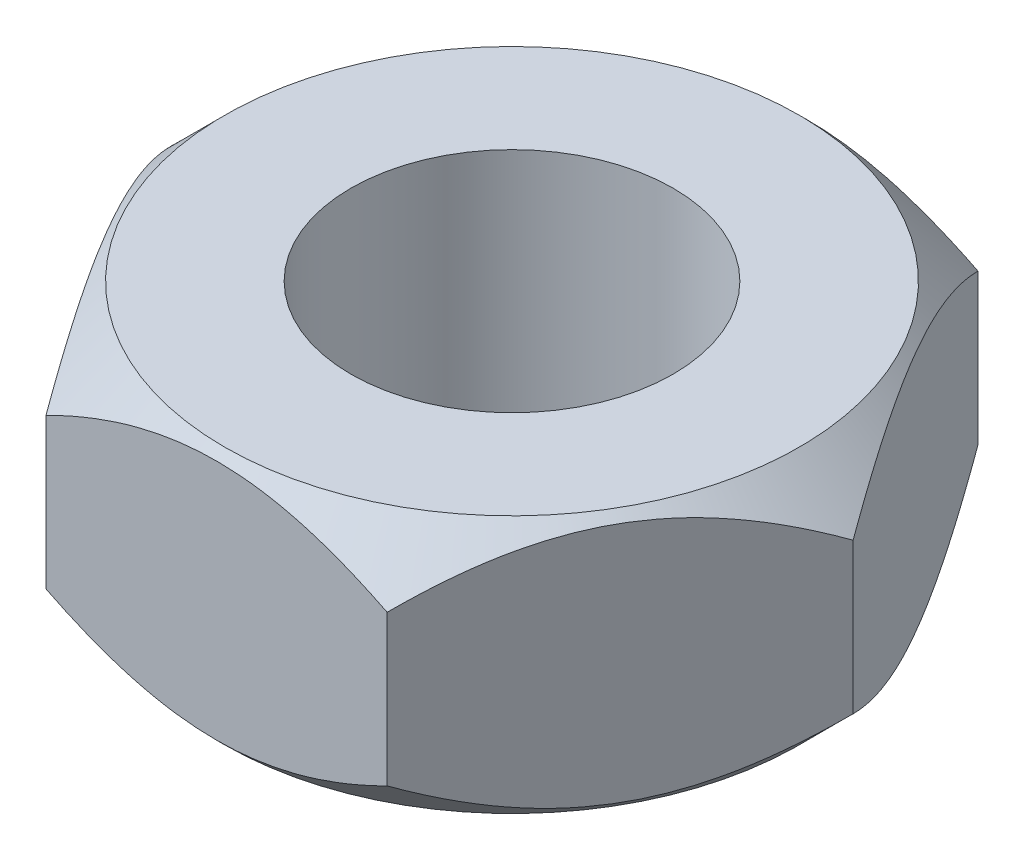
SolidWorks part; units mm, degrees
material "AISI 304"
ref_plane "Front Plane" through (0, 0, 0) normal (0, 0, 1) x (1, 0, 0)
ref_plane "Top Plane" through (0, 0, 0) normal (0, 1, 0) x (1, 0, 0)
ref_plane "Right Plane" through (0, 0, 0) normal (1, 0, 0) x (0, 0, -1)
sketch "Sketch1" plane through (0, 0, 0) normal (0, 1, 0) x (1, 0, 0)
  line L1 (1.5877, 2.75) -> (-1.5877, 2.75)
  line L2 (-1.5877, 2.75) -> (-3.1754, 0)
  line L3 (-3.1754, 0) -> (-1.5877, -2.75)
  line L4 (-1.5877, -2.75) -> (1.5877, -2.75)
  line L5 (1.5877, -2.75) -> (3.1754, 0)
  line L6 (3.1754, 0) -> (1.5877, 2.75)
  circle A0 centre (0, 0) radius 2.75 construction
  circle A1 centre (0, 0) radius 1.5
  dimension "D2" = 3
  dimension "D1" = 5.5
extrude "Boss-Extrude1" add sketch "Sketch1" along normal blind 2.4
sketch "Sketch2" plane through (0, 0, 0) normal (0, 0, 1) x (1, 0, 0)
  line L0 (3.1754, 0) -> (3.1754, 0.5)
  line L1 (3.1754, 2.4) -> (3.1754, 0) construction
  line L2 (3.1754, 0.5) -> (2.6754, 0)
  line L3 (2.6754, 0) -> (3.1754, 0)
  line L4 (1.5877, 1.2) -> (50001.5877, 1.2) construction
  line L5 (1.5877, 2.4) -> (1.5877, 0) construction
  line L6 (2.6754, 2.4) -> (3.1754, 2.4)
  line L7 (3.1754, 1.9) -> (2.6754, 2.4)
  line L8 (3.1754, 2.4) -> (3.1754, 1.9)
  point P10 (1.5877, 1.2)
  dimension "D1" = 0.5
ref_axis "Axis1" through (0, 2.4, 0) along (0, -1, 0)
revolve "Cut-Revolve1" cut sketch "Sketch2" angle 360 about axis through (0, 2.4, 0) along (0, -1, 0)
